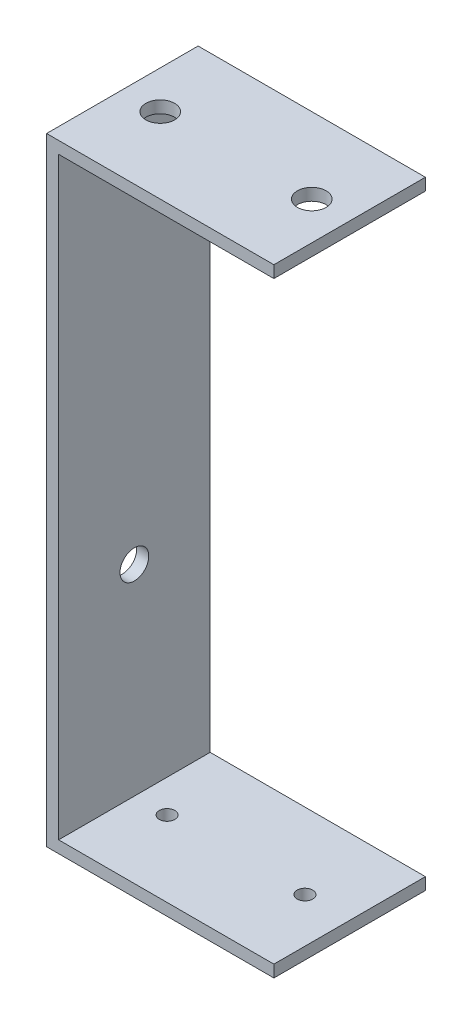
SolidWorks part; units mm, degrees
ref_plane "Front Plane" through (0, 0, 0) normal (0, 0, 1) x (1, 0, 0)
ref_plane "Top Plane" through (0, 0, 0) normal (0, 1, 0) x (1, 0, 0)
ref_plane "Right Plane" through (0, 0, 0) normal (1, 0, 0) x (0, 0, -1)
sketch "Sketch1" plane through (0, 0, 0) normal (0, 0, 1) x (1, 0, 0)
  line L0 (30, 0) -> (0, 0)
  line L1 (0, 0) -> (0, 81.54)
  line L2 (0, 81.54) -> (30, 81.54)
  line L3 (30, 1.5875) -> (1.5875, 1.5875)
  line L4 (1.5875, 1.5875) -> (1.5875, 79.9525)
  line L5 (1.5875, 79.9525) -> (30, 79.9525)
  line L6 (30, 1.5875) -> (30, 0)
  line L7 (30, 81.54) -> (30, 79.9525)
  dimension "D1" = 30
  dimension "D2" = 81.54
  dimension "D3" = 1.5875
extrude "Boss-Extrude1" add sketch "Sketch1" along normal blind 20
hole_wizard "#6 Clearance Hole1" positions "Sketch3" profile "Sketch2" hole size "#6" standard "ANSI Inch"
sketch "Sketch3" plane through (0, 81.54, 0) normal (0, 1, 0) x (1, 0, 0)
  line L2 (15, 3.4) -> (15, -26.541) construction
  point P0 (5, -10)
  point P2 (25, -10)
  dimension "D1" = 10
  dimension "D3" = 20
sketch "Sketch2" plane through (5, 81.54, 10) normal (1, 0, 0) x (0, 0, 1)
  line L0 (0, 0) -> (0, 2.7273)
  line L1 (0, 2.7273) -> (1.8986, 1.5865)
  line L2 (1.8986, 1.5865) -> (1.8986, 0)
  line L5 (1.8986, 0) -> (0, 0)
  line L10 (0, 2.7273) -> (-1.8987, 1.5865) construction
  line L11 (0, -6.35) -> (0, 107.95) construction
  dimension "Hole Dia." = 3.7973
  dimension "Hole Depth" = 1.5865
  dimension "Drill Angle" = 118
hole_wizard "#1 Clearance Hole1" positions "Sketch5" profile "Sketch4" hole size "#1" standard "ANSI Inch"
sketch "Sketch5" plane through (0, 0, 0) normal (0, -1, 0) x (-1, 0, 0)
  line L1 (0, -20) -> (-30, -20) construction
  line L2 (-15, -22.1558) -> (-15, 4.1429) construction
  point P0 (-5.9, -10)
  point P2 (-24.1, -10)
  dimension "D1" = 9.1
  dimension "D2" = 10
  dimension "D3" = 18.2
sketch "Sketch4" plane through (5.9, 0, 10) normal (1, 0, 0) x (0, 0, -1)
  line L0 (0, 0) -> (0, 2.2046)
  line L1 (0, 2.2046) -> (1.0287, 1.5865)
  line L2 (1.0287, 1.5865) -> (1.0287, 0)
  line L5 (1.0287, 0) -> (0, 0)
  line L10 (0, 2.2046) -> (-1.0287, 1.5865) construction
  line L11 (0, -6.35) -> (0, 107.95) construction
  dimension "Hole Dia." = 2.0574
  dimension "Hole Depth" = 1.5865
  dimension "Drill Angle" = 118
hole_wizard "#6 Clearance Hole2" positions "Sketch7" profile "Sketch6" hole size "#6" standard "ANSI Inch"
sketch "Sketch7" plane through (0, 0, 0) normal (-1, 0, 0) x (0, 0, 1)
  line L0 (20, 81.54) -> (20, 0) construction
  line L1 (20, 0) -> (0, 0) construction
  point P0 (10, 28.08)
  point P9 (18.6796, 24.4896)
  dimension "D1" = 10
  dimension "D2" = 28.08
sketch "Sketch6" plane through (0, 28.08, 10) normal (0, 1, 0) x (0, 0, 1)
  line L0 (0, 0) -> (0, 2.7273)
  line L1 (0, 2.7273) -> (1.8986, 1.5865)
  line L2 (1.8986, 1.5865) -> (1.8986, 0)
  line L5 (1.8986, 0) -> (0, 0)
  line L10 (0, 2.7273) -> (-1.8987, 1.5865) construction
  line L11 (0, -6.35) -> (0, 107.95) construction
  dimension "Hole Dia." = 3.7973
  dimension "Hole Depth" = 1.5865
  dimension "Drill Angle" = 118
